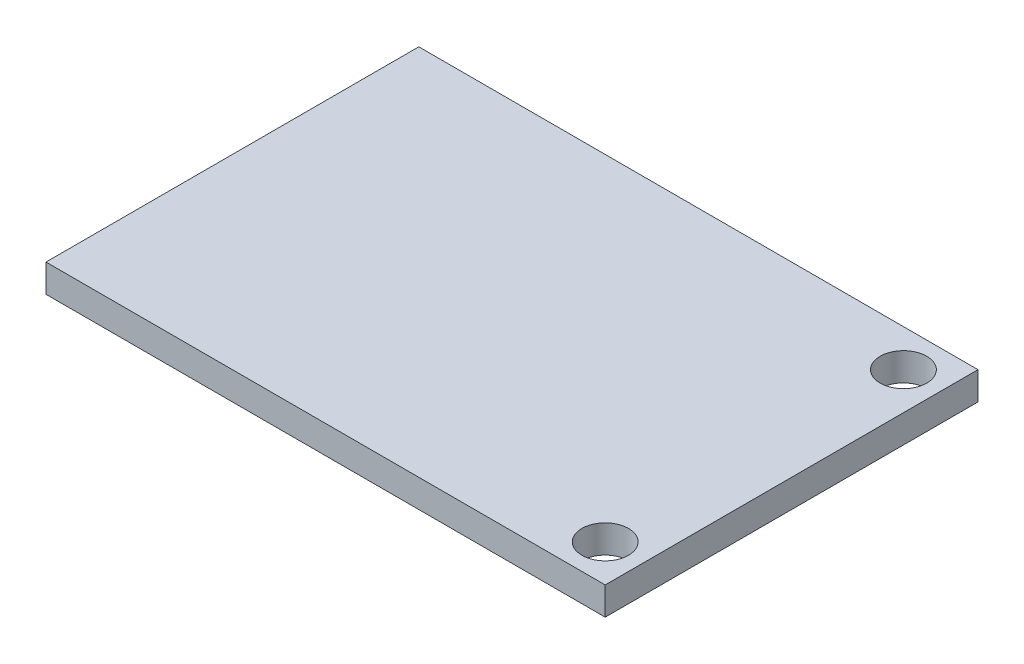
SolidWorks part; units mm, degrees
ref_plane "Front Plane" through (0, 0, 0) normal (0, 0, 1) x (1, 0, 0)
ref_plane "Top Plane" through (0, 0, 0) normal (0, 1, 0) x (1, 0, 0)
ref_plane "Right Plane" through (0, 0, 0) normal (1, 0, 0) x (0, 0, -1)
sketch "Sketch1" plane through (0, 0, 0) normal (0, 1, 0) x (1, 0, 0)
  line L1 (-15, -10) -> (15, -10)
  line L2 (-15, -10) -> (-15, 10)
  line L3 (-15, 10) -> (15, 10)
  line L4 (15, -10) -> (15, 10)
  line L5 (-15, -10) -> (15, 10) construction
  line L6 (-15, 10) -> (15, -10) construction
  point P0 (0, 0)
  dimension "D1" = 20
  dimension "D2" = 30
extrude "Boss-Extrude1" add sketch "Sketch1" along normal blind 1.5 contours L2 L3 L4 L1
sketch "Sketch2" plane through (0, 1.5, 0) normal (0, 1, 0) x (1, 0, 0)
  line L0 (14.25, -8) -> (15, -8) construction
  line L1 (-13, -8) -> (13, -8) construction
  line L2 (-13, -8) -> (-13, 8) construction
  line L3 (-13, 8) -> (13, 8) construction
  line L4 (13, -8) -> (13, 8) construction
  line L5 (-13, -8) -> (13, 8) construction
  line L6 (-13, 8) -> (13, -8) construction
  line L7 (15, -10) -> (15, 10) construction
  line L8 (13, -9.25) -> (13, -10) construction
  line L9 (-15, -10) -> (15, -10) construction
  circle A0 centre (13, 8) radius 1.25
  circle A1 centre (13, -8) radius 1.25
  point P0 (0, 0)
  dimension "D2" = 2.5
  dimension "D1" = 16
extrude "Cut-Extrude1" cut sketch "Sketch2" against normal through all
